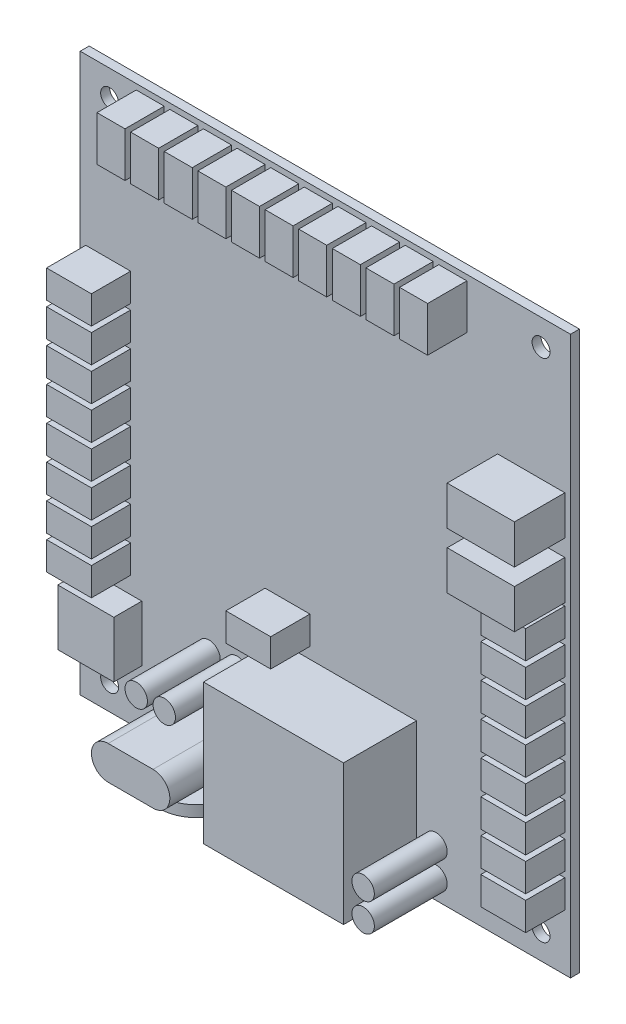
SolidWorks part; units mm, degrees
ref_plane "前视基准面" through (0, 0, 0) normal (0, 0, 1) x (1, 0, 0)
ref_plane "上视基准面" through (0, 0, 0) normal (0, 1, 0) x (1, 0, 0)
ref_plane "右视基准面" through (0, 0, 0) normal (1, 0, 0) x (0, 0, -1)
sketch "草图1" plane through (0, 0, 0) normal (0, 0, 1) x (1, 0, 0)
  line L1 (-43.75, -49.75) -> (43.75, -49.75)
  line L2 (-43.75, -49.75) -> (-43.75, 49.75)
  line L3 (-43.75, 49.75) -> (43.75, 49.75)
  line L4 (43.75, -49.75) -> (43.75, 49.75)
  line L5 (-43.75, -49.75) -> (43.75, 49.75) construction
  line L6 (-43.75, 49.75) -> (43.75, -49.75) construction
  line L7 (-38.5, -45.15) -> (38.5, -45.15) construction
  line L8 (-38.5, -45.15) -> (-38.5, 45.15) construction
  line L9 (-38.5, 45.15) -> (38.5, 45.15) construction
  line L10 (38.5, -45.15) -> (38.5, 45.15) construction
  line L11 (-38.5, -45.15) -> (38.5, 45.15) construction
  line L12 (-38.5, 45.15) -> (38.5, -45.15) construction
  circle A0 centre (-38.5, 45.15) radius 1.6
  circle A1 centre (38.5, 45.15) radius 1.6
  circle A2 centre (-38.5, -45.15) radius 1.6
  circle A3 centre (38.5, -45.15) radius 1.6
  point P0 (0, 0)
  point P6 (0, 0)
  dimension "D5" = 3.2
  dimension "D1" = 87.5
  dimension "D2" = 99.5
  dimension "D3" = 77
  dimension "D4" = 90.3
extrude "凸台-拉伸1" add sketch "草图1" along normal blind 1.6
sketch "草图2" plane through (0, 0, 1.6) normal (0, 0, 1) x (1, 0, 0)
  line L0 (-43.75, -49.75) -> (43.75, -49.75) construction
  line L1 (-42.75, -29.75) -> (-32.75, -29.75)
  line L2 (-42.75, -29.75) -> (-42.75, -39.75)
  line L3 (-42.75, -39.75) -> (-32.75, -39.75)
  line L4 (-32.75, -29.75) -> (-32.75, -39.75)
  line L5 (-43.75, 49.75) -> (-43.75, -49.75) construction
  dimension "D1" = 10
  dimension "D2" = 10
  dimension "D3" = 10
  dimension "D4" = 1
extrude "凸台-拉伸2" add sketch "草图2" along normal blind 5
sketch "草图3" plane through (0, 0, 1.6) normal (0, 0, 1) x (1, 0, 0)
  line L1 (-8.75, -48.75) -> (16.25, -48.75)
  line L2 (-8.75, -48.75) -> (-8.75, -23.75)
  line L3 (-8.75, -23.75) -> (16.25, -23.75)
  line L4 (16.25, -48.75) -> (16.25, -23.75)
  line L5 (-43.75, 49.75) -> (-43.75, -49.75) construction
  line L6 (-43.75, -49.75) -> (43.75, -49.75) construction
  dimension "D1" = 35
  dimension "D2" = 60
  dimension "D3" = 25
  dimension "D4" = 1
extrude "凸台-拉伸3" add sketch "草图3" along normal blind 13
sketch "草图4" plane through (0, 0, 1.6) normal (0, 0, 1) x (1, 0, 0)
  line L0 (43.75, 49.75) -> (-43.75, 49.75) construction
  line L1 (-33.75, 48.75) -> (-28.75, 48.75)
  line L2 (-33.75, 48.75) -> (-33.75, 40.75)
  line L3 (-33.75, 40.75) -> (-28.75, 40.75)
  line L4 (-28.75, 48.75) -> (-28.75, 40.75)
  line L5 (-43.75, 49.75) -> (-43.75, -49.75) construction
  line L6 (-27.75, 48.75) -> (-27.75, 40.75)
  line L7 (-27.75, 48.75) -> (-22.75, 48.75)
  line L8 (-22.75, 48.75) -> (-22.75, 40.75)
  line L9 (-27.75, 40.75) -> (-22.75, 40.75)
  line L10 (-21.75, 48.75) -> (-21.75, 40.75)
  line L11 (-21.75, 48.75) -> (-16.75, 48.75)
  line L12 (-16.75, 48.75) -> (-16.75, 40.75)
  line L13 (-21.75, 40.75) -> (-16.75, 40.75)
  line L14 (-15.75, 48.75) -> (-15.75, 40.75)
  line L15 (-15.75, 48.75) -> (-10.75, 48.75)
  line L16 (-10.75, 48.75) -> (-10.75, 40.75)
  line L17 (-15.75, 40.75) -> (-10.75, 40.75)
  line L18 (-9.75, 48.75) -> (-9.75, 40.75)
  line L19 (-9.75, 48.75) -> (-4.75, 48.75)
  line L20 (-4.75, 48.75) -> (-4.75, 40.75)
  line L21 (-9.75, 40.75) -> (-4.75, 40.75)
  line L22 (-3.75, 48.75) -> (-3.75, 40.75)
  line L23 (-3.75, 48.75) -> (1.25, 48.75)
  line L24 (1.25, 48.75) -> (1.25, 40.75)
  line L25 (-3.75, 40.75) -> (1.25, 40.75)
  line L26 (2.25, 48.75) -> (2.25, 40.75)
  line L27 (2.25, 48.75) -> (7.25, 48.75)
  line L28 (7.25, 48.75) -> (7.25, 40.75)
  line L29 (2.25, 40.75) -> (7.25, 40.75)
  line L30 (8.25, 48.75) -> (8.25, 40.75)
  line L31 (8.25, 48.75) -> (13.25, 48.75)
  line L32 (13.25, 48.75) -> (13.25, 40.75)
  line L33 (8.25, 40.75) -> (13.25, 40.75)
  line L34 (14.25, 48.75) -> (14.25, 40.75)
  line L35 (14.25, 48.75) -> (19.25, 48.75)
  line L36 (19.25, 48.75) -> (19.25, 40.75)
  line L37 (14.25, 40.75) -> (19.25, 40.75)
  line L38 (20.25, 48.75) -> (20.25, 40.75)
  line L39 (20.25, 48.75) -> (25.25, 48.75)
  line L40 (25.25, 48.75) -> (25.25, 40.75)
  line L41 (20.25, 40.75) -> (25.25, 40.75)
  line L42 (-32.75, -29.75) -> (-42.75, -29.75) construction
  line L47 (-42.75, -26.75) -> (-34.75, -26.75)
  line L48 (-42.75, -26.75) -> (-42.75, -21.75)
  line L49 (-42.75, -21.75) -> (-34.75, -21.75)
  line L50 (-34.75, -26.75) -> (-34.75, -21.75)
  line L51 (-42.75, -20.75) -> (-42.75, -15.75)
  line L52 (-42.75, -20.75) -> (-34.75, -20.75)
  line L53 (-34.75, -20.75) -> (-34.75, -15.75)
  line L54 (-42.75, -15.75) -> (-34.75, -15.75)
  line L55 (-42.75, -14.75) -> (-42.75, -9.75)
  line L56 (-42.75, -14.75) -> (-34.75, -14.75)
  line L57 (-34.75, -14.75) -> (-34.75, -9.75)
  line L58 (-42.75, -9.75) -> (-34.75, -9.75)
  line L59 (-42.75, -8.75) -> (-42.75, -3.75)
  line L60 (-42.75, -8.75) -> (-34.75, -8.75)
  line L61 (-34.75, -8.75) -> (-34.75, -3.75)
  line L62 (-42.75, -3.75) -> (-34.75, -3.75)
  line L63 (-42.75, -2.75) -> (-42.75, 2.25)
  line L64 (-42.75, -2.75) -> (-34.75, -2.75)
  line L65 (-34.75, -2.75) -> (-34.75, 2.25)
  line L66 (-42.75, 2.25) -> (-34.75, 2.25)
  line L67 (-42.75, 3.25) -> (-42.75, 8.25)
  line L68 (-42.75, 3.25) -> (-34.75, 3.25)
  line L69 (-34.75, 3.25) -> (-34.75, 8.25)
  line L70 (-42.75, 8.25) -> (-34.75, 8.25)
  line L71 (-42.75, 9.25) -> (-42.75, 14.25)
  line L72 (-42.75, 9.25) -> (-34.75, 9.25)
  line L73 (-34.75, 9.25) -> (-34.75, 14.25)
  line L74 (-42.75, 14.25) -> (-34.75, 14.25)
  line L75 (-42.75, 15.25) -> (-42.75, 20.25)
  line L76 (-42.75, 15.25) -> (-34.75, 15.25)
  line L77 (-34.75, 15.25) -> (-34.75, 20.25)
  line L78 (-42.75, 20.25) -> (-34.75, 20.25)
  line L79 (43.75, -49.75) -> (43.75, 49.75) construction
  line L80 (34.75, -39.75) -> (42.75, -39.75)
  line L81 (34.75, -39.75) -> (34.75, -34.75)
  line L82 (34.75, -34.75) -> (42.75, -34.75)
  line L83 (42.75, -39.75) -> (42.75, -34.75)
  line L84 (-43.75, -49.75) -> (43.75, -49.75) construction
  line L85 (34.75, -33.75) -> (34.75, -28.75)
  line L86 (34.75, -33.75) -> (42.75, -33.75)
  line L87 (42.75, -33.75) -> (42.75, -28.75)
  line L88 (34.75, -28.75) -> (42.75, -28.75)
  line L89 (34.75, -27.75) -> (34.75, -22.75)
  line L90 (34.75, -27.75) -> (42.75, -27.75)
  line L91 (42.75, -27.75) -> (42.75, -22.75)
  line L92 (34.75, -22.75) -> (42.75, -22.75)
  line L93 (34.75, -21.75) -> (34.75, -16.75)
  line L94 (34.75, -21.75) -> (42.75, -21.75)
  line L95 (42.75, -21.75) -> (42.75, -16.75)
  line L96 (34.75, -16.75) -> (42.75, -16.75)
  line L97 (34.75, -15.75) -> (34.75, -10.75)
  line L98 (34.75, -15.75) -> (42.75, -15.75)
  line L99 (42.75, -15.75) -> (42.75, -10.75)
  line L100 (34.75, -10.75) -> (42.75, -10.75)
  line L101 (34.75, -9.75) -> (34.75, -4.75)
  line L102 (34.75, -9.75) -> (42.75, -9.75)
  line L103 (42.75, -9.75) -> (42.75, -4.75)
  line L104 (34.75, -4.75) -> (42.75, -4.75)
  line L105 (34.75, -3.75) -> (34.75, 1.25)
  line L106 (34.75, -3.75) -> (42.75, -3.75)
  line L107 (42.75, -3.75) -> (42.75, 1.25)
  line L108 (34.75, 1.25) -> (42.75, 1.25)
  line L109 (34.75, 2.25) -> (34.75, 7.25)
  line L110 (34.75, 2.25) -> (42.75, 2.25)
  line L111 (42.75, 2.25) -> (42.75, 7.25)
  line L112 (34.75, 7.25) -> (42.75, 7.25)
  line L113 (16.25, -23.75) -> (-8.75, -23.75) construction
  line L114 (-10.75, -21.75) -> (-2.75, -21.75)
  line L115 (-10.75, -21.75) -> (-10.75, -16.75)
  line L116 (-10.75, -16.75) -> (-2.75, -16.75)
  line L117 (-2.75, -21.75) -> (-2.75, -16.75)
  point P6 (-33.75, 44.75)
  dimension "D1" = 5
  dimension "D2" = 8
  dimension "D3" = 1
  dimension "D4" = 10
  dimension "D6" = 6
  dimension "D7" = 5
  dimension "D8" = 8
  dimension "D9" = 1
  dimension "D10" = 3
  dimension "D12" = 6
  dimension "D13" = 1
  dimension "D14" = 10
  dimension "D15" = 8
  dimension "D16" = 5
  dimension "D18" = 8
  dimension "D19" = 5
  dimension "D20" = 2
  dimension "D21" = 2
  dimension "D22" = 6
  dimension "D5" = 10
  dimension "D11" = 8
  dimension "D17" = 8
extrude "凸台-拉伸4" add sketch "草图4" along normal blind 7
sketch "草图5" plane through (0, 0, 1.6) normal (0, 0, 1) x (1, 0, 0)
  line L0 (42.75, 7.25) -> (34.75, 7.25) construction
  line L1 (30.75, 7.75) -> (42.75, 7.75)
  line L2 (30.75, 7.75) -> (30.75, 14.75)
  line L3 (30.75, 14.75) -> (42.75, 14.75)
  line L4 (42.75, 7.75) -> (42.75, 14.75)
  line L5 (43.75, -49.75) -> (43.75, 49.75) construction
  line L6 (30.75, 17.75) -> (30.75, 24.75)
  line L7 (30.75, 17.75) -> (42.75, 17.75)
  line L8 (42.75, 17.75) -> (42.75, 24.75)
  line L9 (30.75, 24.75) -> (42.75, 24.75)
  dimension "D1" = 7
  dimension "D2" = 12
  dimension "D3" = 0.5
  dimension "D4" = 1
  dimension "D6" = 10
  dimension "D5" = 2
extrude "凸台-拉伸5" add sketch "草图5" along normal blind 9
sketch "草图6" plane through (0, 0, 1.6) normal (0, 0, 1) x (1, 0, 0)
  line L0 (-20.75, -39.75) -> (-12.75, -39.75) construction
  line L1 (-20.75, -36.75) -> (-12.75, -36.75)
  line L2 (-20.75, -42.75) -> (-12.75, -42.75)
  line L3 (-8.75, -23.75) -> (-8.75, -48.75) construction
  line L4 (-43.75, -49.75) -> (43.75, -49.75) construction
  arc A0 (-20.75, -36.75) -> (-20.75, -42.75) centre (-20.75, -39.75) ccw
  arc A1 (-12.75, -42.75) -> (-12.75, -36.75) centre (-12.75, -39.75) ccw
  point P2 (-16.75, -39.75)
  dimension "D2" = 3
  dimension "D1" = 8
  dimension "D3" = 4
  dimension "D4" = 10
extrude "凸台-拉伸6" add sketch "草图6" along normal blind 18
sketch "草图7" plane through (0, 0, 1.6) normal (0, 0, 1) x (1, 0, 0)
  circle A0 centre (-20.75, -31.75) radius 2
  circle A1 centre (-15.75, -31.75) radius 2
  circle A2 centre (19.75, -41.25) radius 2
  circle A3 centre (19.75, -46.25) radius 2
  dimension "D1" = 4
  dimension "D2" = 5
  dimension "D3" = 5
  dimension "D4" = 12
  dimension "D5" = 8
  dimension "D6" = 3.5
  dimension "D7" = 2.5
extrude "凸台-拉伸7" add sketch "草图7" along normal blind 13
ref_plane "基准面4" through (0, -47.75, 0) normal (0, -1, 0) x (-1, 0, 0)
sketch "草图8" plane through (0, -47.75, 0) normal (0, -1, 0) x (-1, 0, 0)
  line L0 (33.75, -1.6) -> (28.75, -1.6) construction
  circle A0 centre (17, -7.6) radius 6.5
  dimension "D2" = 13
  dimension "D1" = 6
  dimension "D3" = 17
extrude "凸台-拉伸8" add sketch "草图8" against normal blind 2
